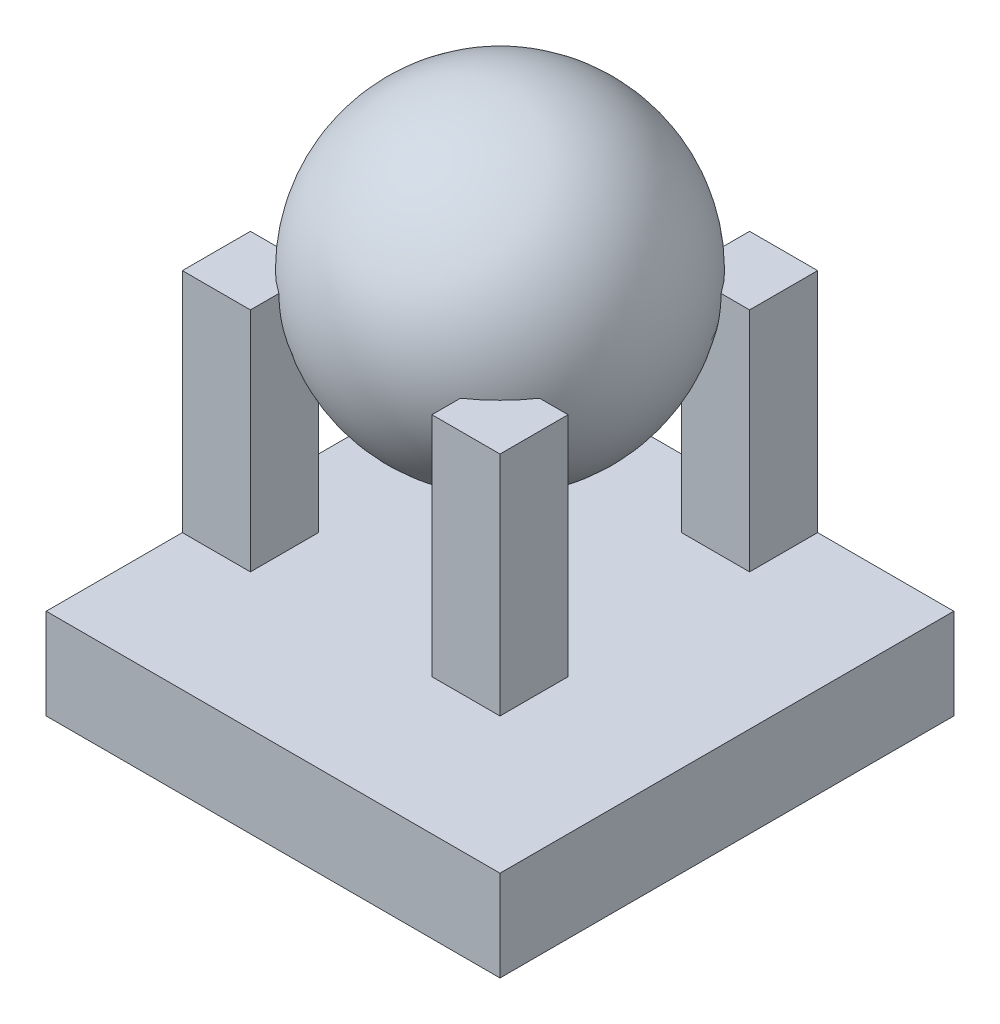
SolidWorks part; units mm, degrees
ref_plane "Alzado" through (0, 0, 0) normal (0, 0, 1) x (1, 0, 0)
ref_plane "Planta" through (0, 0, 0) normal (0, 1, 0) x (1, 0, 0)
ref_plane "Vista lateral" through (0, 0, 0) normal (1, 0, 0) x (0, 0, -1)
sketch "Croquis1" plane through (0, 0, 0) normal (0, 1, 0) x (1, 0, 0)
  line L1 (-50, -50) -> (50, -50)
  line L2 (-50, -50) -> (-50, 50)
  line L3 (-50, 50) -> (50, 50)
  line L4 (50, -50) -> (50, 50)
  line L5 (-50, -50) -> (50, 50) construction
  line L6 (-50, 50) -> (50, -50) construction
  point P0 (0, 0)
  dimension "D1" = 100
  dimension "D2" = 100
extrude "Saliente-Extruir1" add sketch "Croquis1" along normal blind 20
sketch "Croquis2" plane through (0, 20, 0) normal (0, 1, 0) x (1, 0, 0)
  line L0 (-50, -20) -> (-35, -20)
  line L1 (-50, -20) -> (-50, -5)
  line L2 (-50, -5) -> (-35, -5)
  line L3 (-50, 35) -> (-35, 35)
  line L4 (-50, 35) -> (-50, 50)
  line L5 (-50, 50) -> (-35, 50)
  line L6 (-35, 35) -> (-35, 50)
  line L7 (-50, 35) -> (-35, 50) construction
  line L12 (-50, 50) -> (-35, 35) construction
  line L13 (-35, -20) -> (-35, -5)
  line L14 (-50, -20) -> (-35, -5) construction
  line L15 (-50, -5) -> (-35, -20) construction
  line L16 (5, 35) -> (20, 35)
  line L17 (5, 35) -> (5, 50)
  line L18 (5, 50) -> (20, 50)
  line L19 (20, 35) -> (20, 50)
  line L20 (5, 35) -> (20, 50) construction
  line L21 (5, 50) -> (20, 35) construction
  line L22 (5, -20) -> (20, -20)
  line L23 (5, -20) -> (5, -5)
  line L24 (5, -5) -> (20, -5)
  line L25 (20, -20) -> (20, -5)
  line L26 (5, -20) -> (20, -5) construction
  line L27 (5, -5) -> (20, -20) construction
  line L28 (50, 50) -> (-50, 50) construction
  line L29 (-50, 50) -> (-50, -50) construction
  point P0 (-42.5, -12.5)
  point P5 (12.5, 42.5)
  point P6 (-42.5, 42.5)
  point P16 (12.5, -12.5)
  point P23 (5.5397, 42.5)
  point P24 (-34.4084, 3.433)
  point P25 (13.0397, 4.3693)
  dimension "D1" = 15
  dimension "D2" = 15
  dimension "D3" = 15
  dimension "D4" = 15
  dimension "D5" = 15
  dimension "D6" = 15
  dimension "D7" = 15
  dimension "D8" = 15
  dimension "D9" = 70
  dimension "D10" = 70
extrude "Saliente-Extruir2" add sketch "Croquis2" along normal blind 50
ref_plane "Plano1" through (0, 0, -15) normal (0, 0, 1) x (1, 0, 0)
sketch "Croquis4" plane through (0, 0, -15) normal (0, 0, 1) x (1, 0, 0)
  line L0 (-50, 70) -> (-50, 20) construction
  line L1 (20, 70) -> (20, 20) construction
  line L2 (-50, 70) -> (-50, 20) construction
  line L3 (20, 70) -> (20, 20) construction
  line L4 (-15, 35) -> (-15, 105) construction
  line L5 (-15, 105) -> (-15, 35)
  arc A0 (-15, 105) -> (-15, 35) centre (-15, 70) ccw
  dimension "D2" = 70
  dimension "D1" = 35
revolve "Revolución1" add sketch "Croquis4" angle 360 about L5
